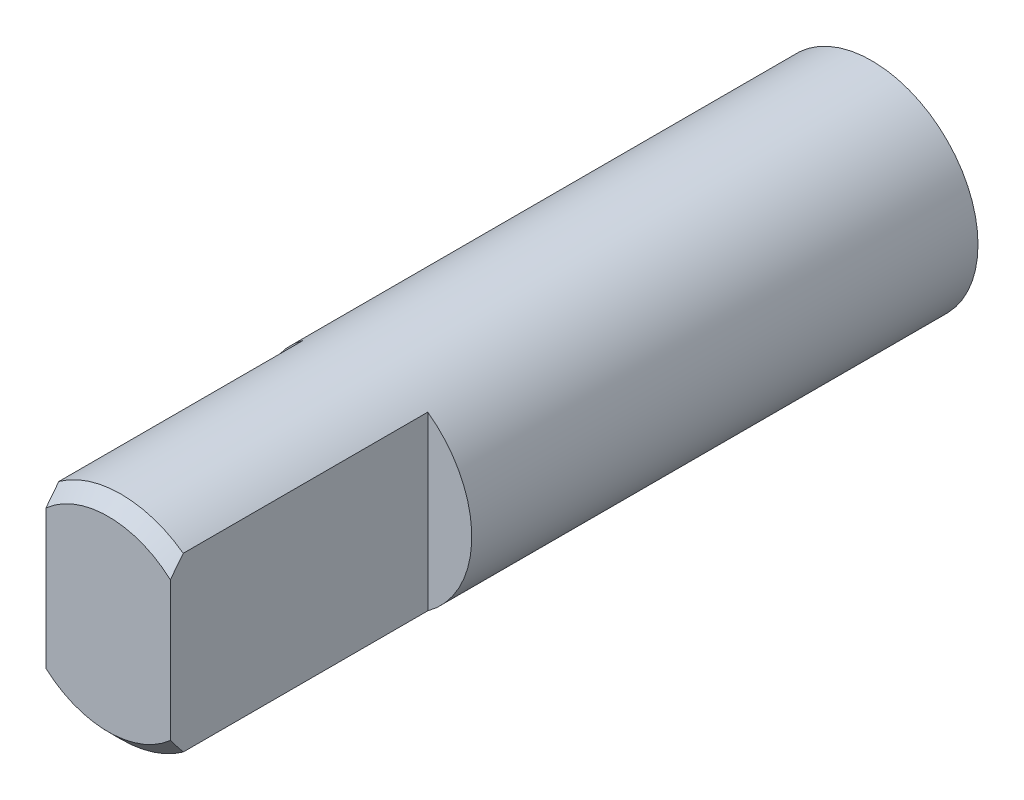
SolidWorks part; units mm, degrees
material "Латунь"
ref_plane "Front Plane" through (0, 0, 0) normal (0, 0, 1) x (1, 0, 0)
ref_plane "Top Plane" through (0, 0, 0) normal (0, 1, 0) x (1, 0, 0)
ref_plane "Right Plane" through (0, 0, 0) normal (1, 0, 0) x (0, 0, -1)
sketch "Sketch1" plane through (0, 0, 0) normal (0, 0, 1) x (1, 0, 0)
  circle A0 centre (0, 0) radius 2.475
  dimension "D1" = 4.95
extrude "Extrude1" add sketch "Sketch1" along normal blind 17.8
sketch "Sketch2" plane through (0, 0, 17.8) normal (0, 0, 1) x (1, 0, 0)
  line L1 (-1.45, 3.5) -> (1.45, 3.5)
  line L2 (-1.45, 3.5) -> (-1.45, -3.5)
  line L3 (-1.45, -3.5) -> (1.45, -3.5)
  line L4 (1.45, 3.5) -> (1.45, -3.5)
  line L5 (-1.45, 3.5) -> (1.45, -3.5) construction
  line L6 (-1.45, -3.5) -> (1.45, 3.5) construction
  point P0 (0, 0)
  dimension "D1" = 7
  dimension "D2" = 2.9
extrude "Extrude2" cut sketch "Sketch2" against normal blind 6 flip side to cut
chamfer "Chamfer1" distance 0.3 angle 45 2 edges at (0, -2.475, 17.8) (0, 2.475, 17.8)
